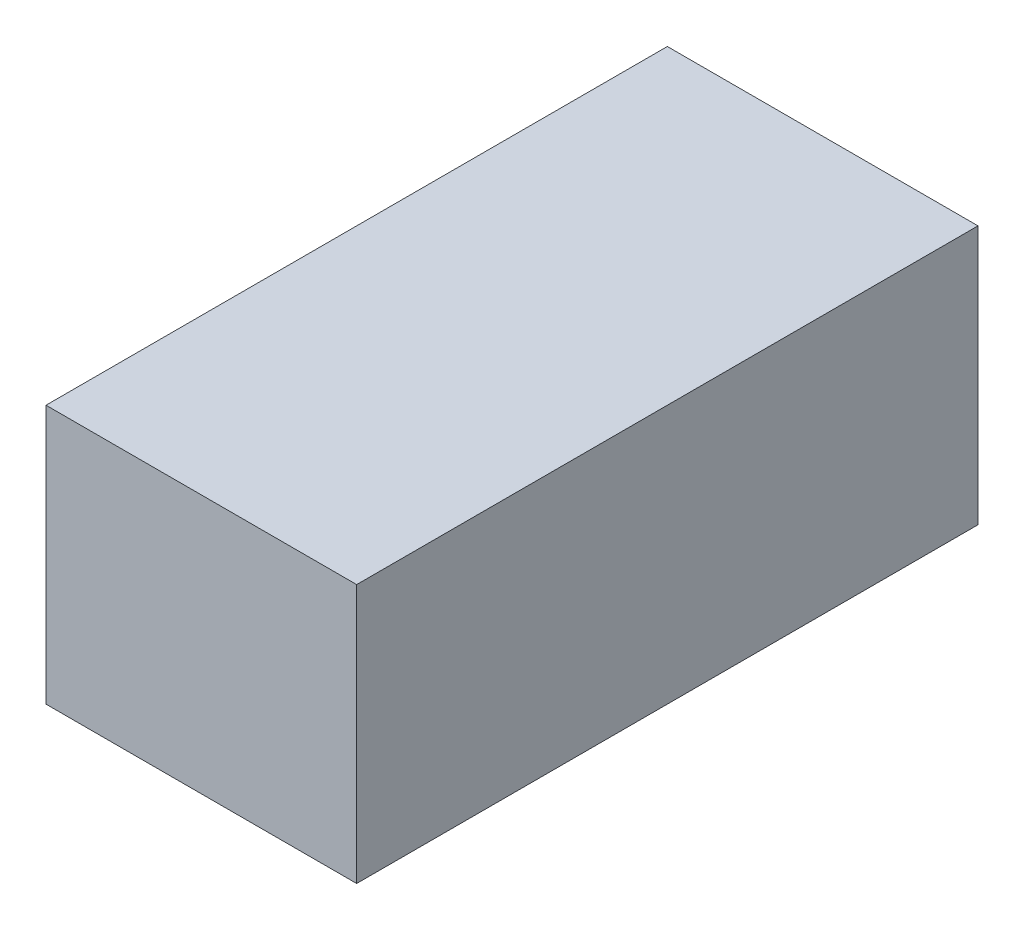
SolidWorks part; units mm, degrees
ref_plane "front" through (0, 0, 0) normal (0, 0, 1) x (1, 0, 0)
ref_plane "top" through (0, 0, 0) normal (0, 1, 0) x (1, 0, 0)
ref_plane "right" through (0, 0, 0) normal (1, 0, 0) x (0, 0, -1)
sketch "Sketch2" plane through (0, 0, 0) normal (0, 1, 0) x (1, 0, 0)
  line L0 (-19.05, 0) -> (19.05, 0)
  line L3 (19.05, 0) -> (19.05, 76.2)
  line L4 (19.05, 76.2) -> (-19.05, 76.2)
  line L5 (-19.05, 76.2) -> (-19.05, 0)
  point P2 (0, 0)
  point P11 (0, 76.2)
  dimension "D1" = 76.2
  dimension "D3" = 38.1
extrude "Extrude1" add sketch "Sketch2" along normal blind 31.75
